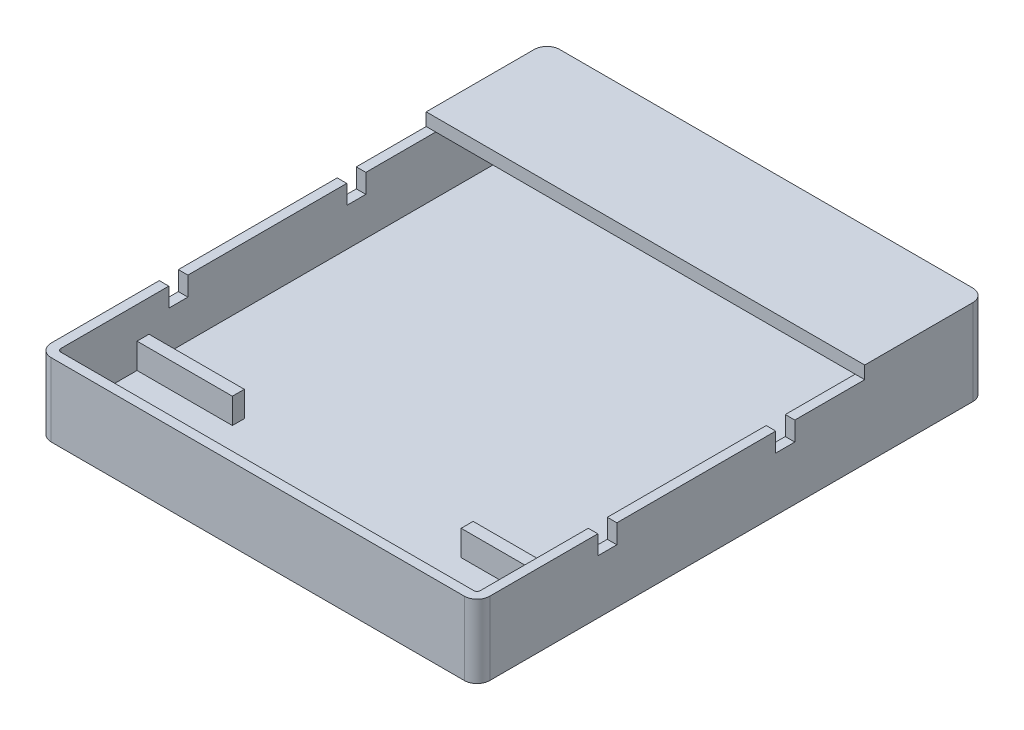
SolidWorks part; units mm, degrees
ref_plane "前视基准面" through (0, 0, 0) normal (0, 0, 1) x (1, 0, 0)
ref_plane "上视基准面" through (0, 0, 0) normal (0, 1, 0) x (1, 0, 0)
ref_plane "右视基准面" through (0, 0, 0) normal (1, 0, 0) x (0, 0, -1)
other "Configuration Table"
sketch "草图1" plane through (0, 0, 0) normal (0, 1, 0) x (1, 0, 0)
  line L1 (-32.5, 40) -> (32.5, 40)
  line L2 (-34.5, 38) -> (-34.5, -38)
  line L3 (-32.5, -40) -> (32.5, -40)
  line L4 (34.5, 38) -> (34.5, -38)
  line L5 (-34.5, 40) -> (34.5, -40) construction
  line L6 (-34.5, -40) -> (34.5, 40) construction
  arc A0 (-34.5, -38) -> (-32.5, -40) centre (-32.5, -38) ccw
  arc A1 (32.5, -40) -> (34.5, -38) centre (32.5, -38) ccw
  arc A2 (32.5, 40) -> (34.5, 38) centre (32.5, 38) cw
  arc A3 (-32.5, 40) -> (-34.5, 38) centre (-32.5, 38) ccw
  point P0 (0, 0)
  dimension "D3" = 2
  dimension "D1" = 80
  dimension "D2" = 69
extrude "凸台-拉伸1" add sketch "草图1" along normal blind 2.5
sketch "草图2" plane through (0, 2.5, 0) normal (0, 1, 0) x (1, 0, 0)
  line L8 (-32.5, -38.5) -> (32.5, -38.5)
  line L9 (33, -38) -> (33, 38)
  line L10 (32.5, 38.5) -> (-32.5, 38.5)
  line L11 (-33, 38) -> (-33, -38)
  line L12 (-32.5, -38.5) -> (32.5, -38.5)
  line L13 (33, -38) -> (33, 38)
  line L14 (32.5, 38.5) -> (-32.5, 38.5)
  line L15 (-33, 38) -> (-33, -38)
  line L37 (-32.5, -40) -> (32.5, -40)
  line L38 (34.5, -38) -> (34.5, 38)
  line L39 (32.5, 40) -> (-32.5, 40)
  line L40 (-34.5, 38) -> (-34.5, -38)
  line L41 (-32.5, -40) -> (32.5, -40)
  line L42 (34.5, -38) -> (34.5, 38)
  line L43 (32.5, 40) -> (-32.5, 40)
  line L44 (-34.5, 38) -> (-34.5, -38)
  arc A8 (-33, -38) -> (-32.5, -38.5) centre (-32.5, -38) ccw
  arc A9 (32.5, -38.5) -> (33, -38) centre (32.5, -38) ccw
  arc A10 (33, 38) -> (32.5, 38.5) centre (32.5, 38) ccw
  arc A11 (-32.5, 38.5) -> (-33, 38) centre (-32.5, 38) ccw
  arc A12 (-33, -38) -> (-32.5, -38.5) centre (-32.5, -38) ccw
  arc A13 (32.5, -38.5) -> (33, -38) centre (32.5, -38) ccw
  arc A14 (33, 38) -> (32.5, 38.5) centre (32.5, 38) ccw
  arc A15 (-32.5, 38.5) -> (-33, 38) centre (-32.5, 38) ccw
  arc A31 (32.5, -40) -> (34.5, -38) centre (32.5, -38) ccw
  arc A32 (-34.5, -38) -> (-32.5, -40) centre (-32.5, -38) ccw
  arc A33 (34.5, 38) -> (32.5, 40) centre (32.5, 38) ccw
  arc A34 (-32.5, 40) -> (-34.5, 38) centre (-32.5, 38) ccw
  arc A35 (32.5, -40) -> (34.5, -38) centre (32.5, -38) ccw
  arc A36 (-34.5, -38) -> (-32.5, -40) centre (-32.5, -38) ccw
  arc A37 (34.5, 38) -> (32.5, 40) centre (32.5, 38) ccw
  arc A38 (-32.5, 40) -> (-34.5, 38) centre (-32.5, 38) ccw
  dimension "D1" = 1.5
  dimension "D2" = 0
extrude "凸台-拉伸2" add sketch "草图2" along normal blind 9
sketch "草图6" plane through (0, 0, -40) normal (0, 0, -1) x (-1, 0, 0)
  line L0 (-1.5, 2.5) -> (12.5, 2.5)
  line L2 (-18.5, 7.5) -> (-18.5, 2.5)
  line L3 (-18.5, 2.5) -> (-9.5, 2.5)
  line L4 (12.5, 10.5) -> (12.5, 2.5)
  line L5 (-32.5, 11.5) -> (-32.5, 2.5) construction
  line L6 (32.5, 11.5) -> (32.5, 2.5) construction
  line L10 (-18.5, 7.5) -> (-9.5, 7.5)
  line L13 (-9.5, 7.5) -> (-9.5, 2.5)
  line L15 (-1.5, 10.5) -> (-1.5, 2.5)
  line L18 (-1.5, 10.5) -> (12.5, 10.5)
  dimension "D2" = 14
  dimension "D3" = 20
  dimension "D4" = 5
  dimension "D5" = 8
  dimension "D6" = 8
extrude "切除-拉伸3" cut sketch "草图6" against normal blind 9
sketch "草图7" plane through (-33, 0, 0) normal (1, 0, 0) x (0, 0, -1)
  line L0 (38, 2.5) -> (-38, 2.5) construction
  line L1 (28.7713, 4.6) -> (38.7713, 4.6)
  line L2 (28.7713, 4.6) -> (28.7713, 6.1)
  line L3 (28.7713, 6.1) -> (38.7713, 6.1)
  line L4 (38.7713, 4.6) -> (38.7713, 6.1)
  dimension "D1" = 2.1
  dimension "D2" = 1.5
  dimension "D3" = 10
extrude "凸台-拉伸3" add sketch "草图7" along normal blind 1 contours L2 L1 L4 L3
mirror "镜向1" about plane through (0, 0, 0) normal (1, 0, 0) of "凸台-拉伸3"
sketch "草图8" plane through (34.5, 0, 0) normal (1, 0, 0) x (0, 0, -1)
  line L0 (-38, 11.5) -> (38, 11.5) construction
  line L1 (10, 11.5) -> (7, 11.5)
  line L2 (10, 11.5) -> (10, 8.5)
  line L3 (10, 8.5) -> (7, 8.5)
  line L4 (7, 11.5) -> (7, 8.5)
  line L5 (40, 11.5) -> (40, 0) construction
  line L7 (-18, 11.5) -> (-21, 11.5)
  line L8 (-18, 11.5) -> (-18, 8.5)
  line L9 (-18, 8.5) -> (-21, 8.5)
  line L10 (-21, 11.5) -> (-21, 8.5)
  dimension "D1" = 3
  dimension "D2" = 3
  dimension "D3" = 30
  dimension "D4" = 3
  dimension "D5" = 3
  dimension "D6" = 25
extrude "切除-拉伸4" cut sketch "草图8" against normal blind 5
mirror "镜向2" about plane through (0, 0, 0) normal (1, 0, 0) of "切除-拉伸4"
sketch "草图9" plane through (0, 11.5, 0) normal (0, 1, 0) x (1, 0, 0)
  line L0 (-34.5, 38) -> (-34.5, 10) construction
  line L1 (-34.5, 21) -> (34.5, 21)
  line L2 (-34.5, 21) -> (-34.5, 38)
  line L3 (-32.5, 40) -> (32.5, 40)
  line L4 (34.5, 21) -> (34.5, 38)
  line L5 (-33, 10) -> (-34.5, 10) construction
  arc A0 (32.5, 40) -> (34.5, 38) centre (32.5, 38) cw
  arc A1 (-34.5, 38) -> (-32.5, 40) centre (-32.5, 38) cw
  dimension "D2" = 2
  dimension "D3" = 2
  dimension "D1" = 11
extrude "凸台-拉伸4" add sketch "草图9" along normal blind 2
sketch "草图10" plane through (0, 2.5, 0) normal (0, 1, 0) x (1, 0, 0)
  line L0 (-33, 38) -> (-33, -38) construction
  line L1 (-33, -24.116) -> (-18, -24.116)
  line L2 (-33, -24.116) -> (-33, -26)
  line L3 (-33, -26) -> (-18, -26)
  line L4 (33, -24.116) -> (33, -26)
  line L5 (33, -38) -> (33, -21) construction
  line L6 (-12.5, 38.5) -> (-32.5, 38.5) construction
  line L7 (18, -24.116) -> (33, -24.116)
  line L9 (-18, -26) -> (-18, -24.116)
  line L11 (18, -26) -> (18, -24.116)
  line L12 (18, -26) -> (33, -26)
  dimension "D1" = 64.5
  dimension "D2" = 15
  dimension "D3" = 15
extrude "凸台-拉伸5" add sketch "草图10" along normal blind 4
